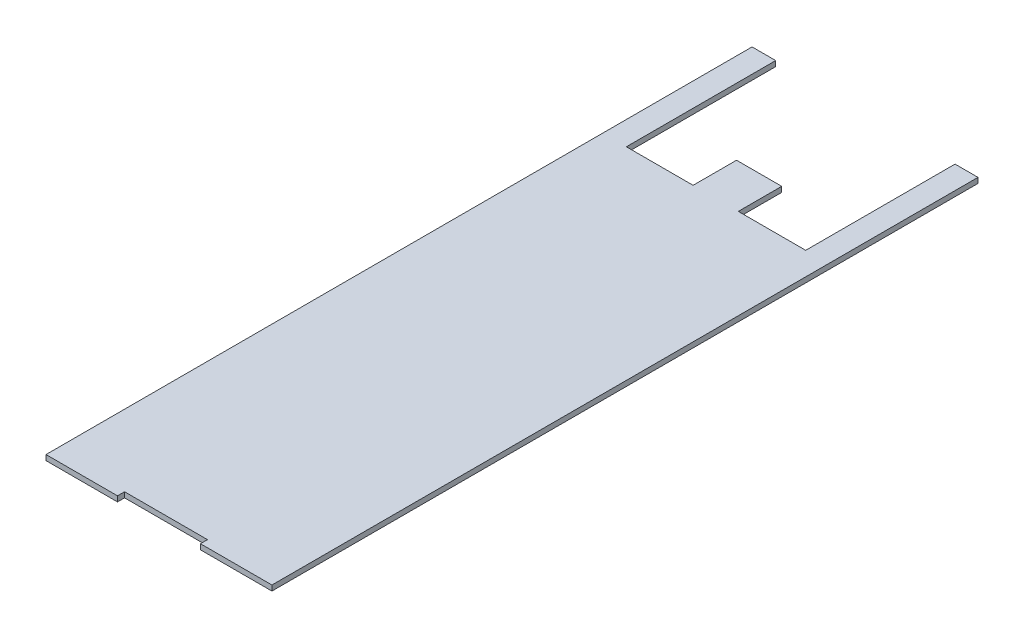
SolidWorks part; units mm, degrees
ref_plane "Front Plane" through (0, 0, 0) normal (0, 0, 1) x (1, 0, 0)
ref_plane "Top Plane" through (0, 0, 0) normal (0, 1, 0) x (1, 0, 0)
ref_plane "Right Plane" through (0, 0, 0) normal (1, 0, 0) x (0, 0, -1)
sketch "Sketch1" plane through (0, -548.2989, 0) normal (0, -1, 0) x (1, 0, 0)
  line L0 (-172.2108, 789.6201) -> (-178.2108, 789.6201) construction
  line L1 (-175.2108, 789.6201) -> (-47.2108, 789.6201)
  line L2 (-175.2108, 789.6201) -> (-175.2108, 389.6201)
  line L3 (-175.2108, 389.6201) -> (-161.8182, 389.6201)
  line L4 (-47.2108, 789.6201) -> (-47.2108, 389.6201)
  line L5 (-50.2108, 389.6201) -> (-44.2108, 389.6201) construction
  line L6 (-98.2108, 472.6201) -> (-98.2108, 454.6201) construction
  line L8 (-60.2182, 389.6201) -> (-47.2108, 389.6201)
  line L9 (-161.8182, 474.2201) -> (-124.0108, 474.2201)
  line L10 (-161.8182, 474.2201) -> (-161.8182, 389.6201)
  line L12 (-60.2182, 474.2201) -> (-60.2182, 389.6201)
  line L13 (-124.0108, 474.2201) -> (-124.0108, 449.6201)
  line L14 (-124.0108, 449.6201) -> (-98.4108, 449.6201)
  line L15 (-98.4108, 474.2201) -> (-98.4108, 449.6201)
  line L16 (-124.2108, 472.6201) -> (-124.2108, 454.6201) construction
  line L17 (-98.4108, 474.2201) -> (-60.2182, 474.2201)
  dimension "D1" = 84.6
  dimension "D2" = 0.2
  dimension "D3" = 0.2
  dimension "D4" = 24.6
extrude "Boss-Extrude1" add sketch "Sketch1" along normal blind 3
sketch "Sketch2" plane through (0, -548.2989, 0) normal (0, 1, 0) x (1, 0, 0)
  line L0 (-47.2108, -789.6201) -> (-175.2108, -789.6201) construction
  line L1 (-134.7108, -793.6201) -> (-87.7108, -793.6201)
  line L2 (-134.7108, -793.6201) -> (-134.7108, -785.6201)
  line L3 (-134.7108, -785.6201) -> (-87.7108, -785.6201)
  line L4 (-87.7108, -793.6201) -> (-87.7108, -785.6201)
  line L5 (-134.7108, -793.6201) -> (-87.7108, -785.6201) construction
  line L6 (-134.7108, -785.6201) -> (-87.7108, -793.6201) construction
  point P0 (-111.2108, -789.6201)
  dimension "D1" = 8
  dimension "D2" = 47
extrude "Cut-Extrude1" cut sketch "Sketch2" against normal blind 10
